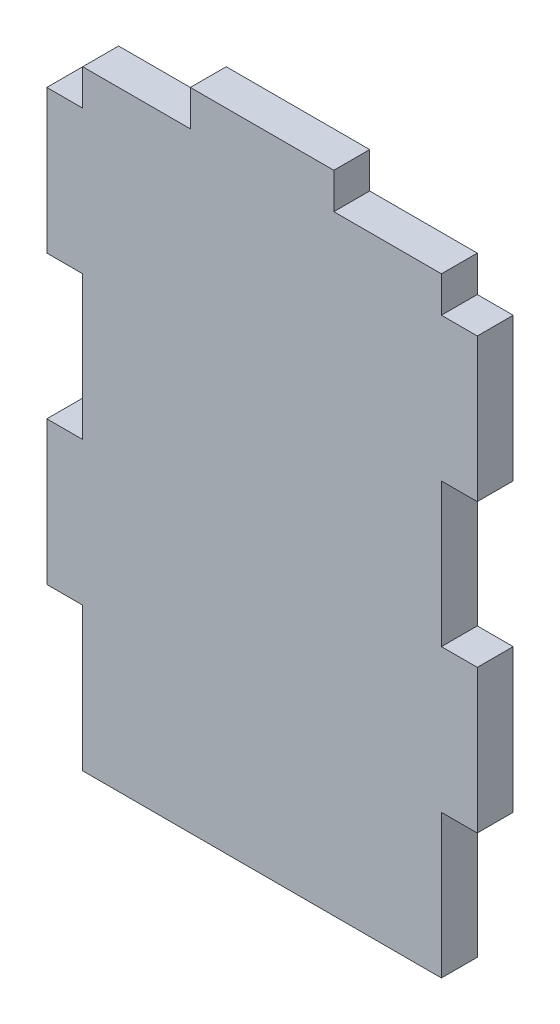
SolidWorks part; units mm, degrees
ref_plane "정면" through (0, 0, 0) normal (0, 0, 1) x (1, 0, 0)
ref_plane "윗면" through (0, 0, 0) normal (0, 1, 0) x (1, 0, 0)
ref_plane "우측면" through (0, 0, 0) normal (1, 0, 0) x (0, 0, -1)
sketch "스케치1" plane through (0, 0, 0) normal (0, 0, 1) x (1, 0, 0)
  line L1 (-25, 42.5) -> (25, 42.5)
  line L2 (-25, 42.5) -> (-25, -42.5)
  line L3 (-25, -42.5) -> (25, -42.5)
  line L4 (25, 42.5) -> (25, -42.5)
  line L5 (-25, 42.5) -> (25, -42.5) construction
  line L6 (-25, -42.5) -> (25, 42.5) construction
  point P0 (0, 0)
  dimension "D1" = 85
  dimension "D2" = 50
extrude "보스-돌출1" add sketch "스케치1" along normal blind 5
sketch "스케치2" plane through (0, 0, 5) normal (0, 0, 1) x (1, 0, 0)
  line L0 (-25, 42.5) -> (-25, -42.5) construction
  line L1 (-25, -22.5) -> (-30, -22.5)
  line L2 (-25, -22.5) -> (-25, -2.5)
  line L3 (-25, -2.5) -> (-30, -2.5)
  line L4 (-30, -22.5) -> (-30, -2.5)
  line L5 (-25, -42.5) -> (25, -42.5) construction
  dimension "D1" = 20
  dimension "D2" = 20
  dimension "D3" = 5
extrude "보스-돌출2" add sketch "스케치2" against normal up to surface (5 mm away) up to face at (0, 0, 0)
pattern_linear "선형 패턴1" count 2 spacing 40 along (0, 1, 0) of "보스-돌출2"
mirror "대칭 복사1" about plane through (0, 0, 0) normal (1, 0, 0) of "선형 패턴1", "보스-돌출2"
sketch "스케치4" plane through (0, 0, 5) normal (0, 0, 1) x (1, 0, 0)
  line L0 (25, 42.5) -> (-25, 42.5) construction
  line L1 (-10, 42.5) -> (10, 42.5)
  line L2 (-10, 42.5) -> (-10, 47.5)
  line L3 (-10, 47.5) -> (10, 47.5)
  line L4 (10, 42.5) -> (10, 47.5)
  line L5 (0, 49.1173) -> (0, 28.671) construction
  dimension "D1" = 20
  dimension "D2" = 5
extrude "보스-돌출3" add sketch "스케치4" against normal up to surface (5 mm away) up to face at (0, 6, 0)
